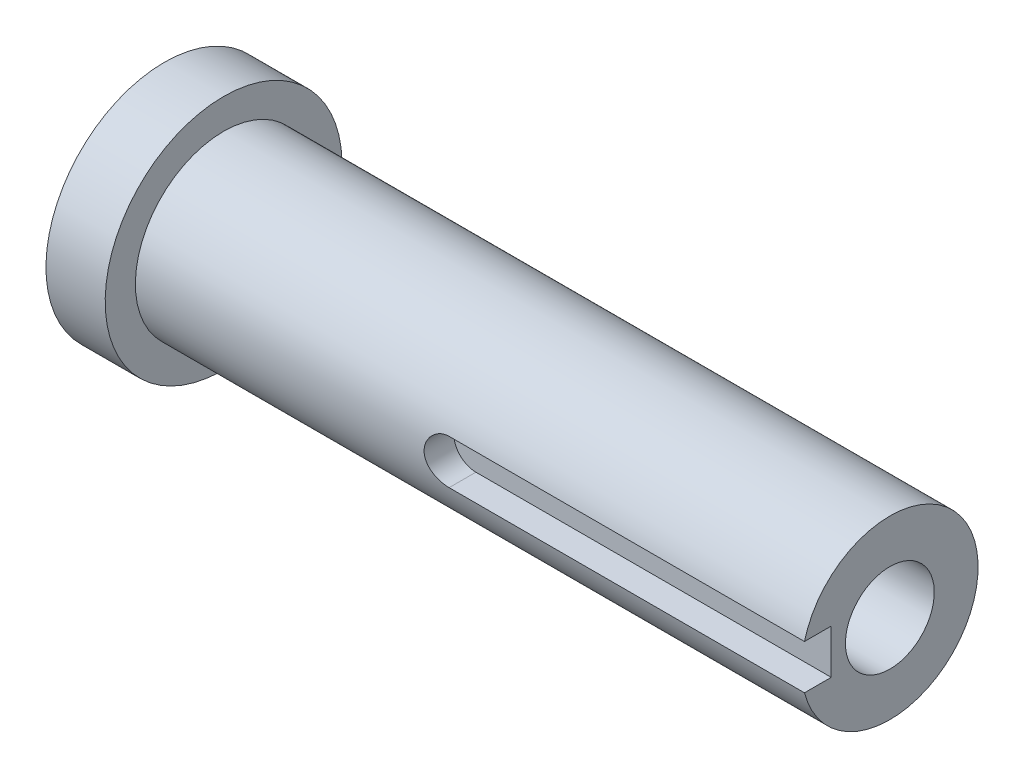
SolidWorks part; units mm, degrees
ref_plane "Front Plane" through (0, 0, 0) normal (0, 0, 1) x (1, 0, 0)
ref_plane "Top Plane" through (0, 0, 0) normal (0, 1, 0) x (1, 0, 0)
ref_plane "Right Plane" through (0, 0, 0) normal (1, 0, 0) x (0, 0, -1)
sketch "Sketch1" plane through (0, 0, 0) normal (0, 0, 1) x (1, 0, 0)
  line L0 (0, 0) -> (0, 25.4)
  line L1 (0, 25.4) -> (12.7, 25.4)
  line L2 (12.7, 25.4) -> (12.7, 18.923)
  line L3 (12.7, 18.923) -> (155.575, 18.923)
  line L4 (155.575, 18.923) -> (155.575, 0)
  line L5 (155.575, 0) -> (0, 0)
  dimension "D1" = 12.7
  dimension "D2" = 142.875
  dimension "D3" = 18.923
  dimension "D4" = 25.4
revolve "Revolve1" add sketch "Sketch1" angle 360 about L5
ref_plane "Plane1" through (0, 0, 18.923) normal (0, 0, 1) x (1, 0, 0)
sketch "Sketch2" plane through (0, 0, 18.923) normal (0, 0, 1) x (1, 0, 0)
  line L0 (155.575, 0) -> (0, 0) construction
  line L1 (155.575, 0) -> (0, 0)
  line L2 (155.575, -18.923) -> (155.575, 18.923) construction
  line L3 (155.575, -18.923) -> (155.575, 18.923)
  line L4 (155.575, 4.7625) -> (79.375, 4.7625)
  line L5 (79.375, -4.7625) -> (155.575, -4.7625)
  arc A0 (79.375, 4.7625) -> (79.375, -4.7625) centre (79.375, 0) ccw
  dimension "D1" = 76.2
  dimension "D2" = 9.525
extrude "Cut-Extrude1" cut sketch "Sketch2" against normal blind 6.35 contours L4 A0 L1 L3 | L1 A0 L5 L3
sketch "Sketch3" plane through (0, 0, 0) normal (-1, 0, 0) x (0, 0, 1)
  circle A0 centre (0, 0) radius 9.525
  dimension "D1" = 19.05
extrude "Cut-Extrude2" cut sketch "Sketch3" against normal through all
